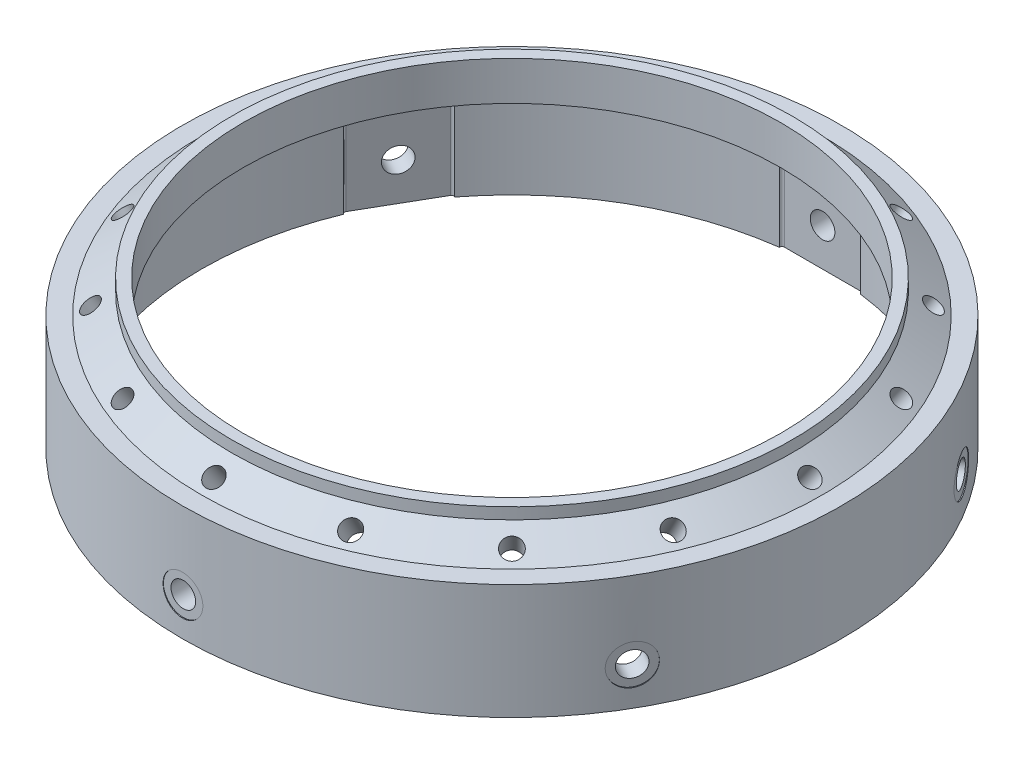
SolidWorks part; units mm, degrees
material "6061 Alloy"
ref_plane "Front Plane" through (0, 0, 0) normal (0, 0, 1) x (1, 0, 0)
ref_plane "Top Plane" through (0, 0, 0) normal (0, 1, 0) x (1, 0, 0)
ref_plane "Right Plane" through (0, 0, 0) normal (1, 0, 0) x (0, 0, -1)
sketch "Sketch1" plane through (0, 0, 0) normal (0, 0, 1) x (1, 0, 0)
  line L9 (0, 0) -> (0, -25.8501) construction
  line L18 (-87, 1) -> (-82, 1)
  line L19 (-82, 1) -> (-74, 6.6017)
  line L20 (-74, 6.6017) -> (-74, 9.6017)
  line L21 (-74, 9.6017) -> (-71, 9.6017)
  line L33 (-71, 9.6017) -> (-71, -0.6981)
  line L34 (-82, -8.4004) -> (-71, -0.6981)
  line L39 (-82, -8.4004) -> (-82, -29.4004)
  line L41 (-82, -29.4004) -> (-87, -29.4004)
  line L42 (-87, -29.4004) -> (-87, 1)
  dimension "D8" = 3
  dimension "D11" = 3
  dimension "D12" = 5
revolve "Revolve1" add sketch "Sketch1" angle 360 about L9
sketch "Sketch2" plane through (0, 0, 0) normal (0, 0, 1) x (1, 0, 0)
  line L0 (-74, 6.6017) -> (-82, 1) construction
  line L1 (-74, 6.6017) -> (-74, 1) construction
  line L2 (-74, 1) -> (-82, 1) construction
  point P4 (-78.671, 3.331)
  dimension "D1" = 4.671
hole_wizard "Ø4.2mm Dowel Hole1" positions "3DSketch1" profile "Sketch3" hole size "Ø5.0" standard "DIN" end condition up to next
sketch3d "3DSketch1"
  point P0 (-78.671, 3.331, 0)
sketch "Sketch3" plane through (-78.671, 3.331, 0) normal (0, 0, 1) x (-0.8192, -0.5736, 0)
  line L0 (0, 0) -> (0, 7.7004)
  line L1 (0, 7.7004) -> (2.5, 7.7004)
  line L2 (2.5, 7.7004) -> (2.5, 0)
  line L5 (2.5, 0) -> (0, 0)
  line L11 (0, -6.35) -> (0, 107.95) construction
  dimension "Thru Hole Dia." = 5
  dimension "Thru Hole Depth" = 7.7004
pattern_circular "CirPattern1" count 16 over 360 about axis through (0, 6.6017, 0) along (0, -1, 0) of "Ø4.2mm Dowel Hole1"
sketch "Szkic4" plane through (0, -29.4004, 0) normal (0, -1, 0) x (-1, 0, 0)
  line L0 (-4, -87) -> (4, -87)
  line L1 (0, -87) -> (0, -84.0434)
  line L2 (0, -84.0434) -> (4, -85.4333)
  line L3 (4, -85.4333) -> (4, -87)
  line L4 (-4, -85.4333) -> (-4, -87)
  line L5 (0, -84.0434) -> (-4, -85.4333)
  line L31 (-77.3442, -40.0359) -> (-73.3442, -46.9641)
  line L32 (-71.9874, -46.1808) -> (-73.3442, -46.9641)
  line L33 (-72.7837, -42.0217) -> (-71.9874, -46.1808)
  line L34 (-72.7837, -42.0217) -> (-75.9874, -39.2526)
  line L35 (-75.9874, -39.2526) -> (-77.3442, -40.0359)
  line L36 (-73.3442, 46.9641) -> (-77.3442, 40.0359)
  line L37 (-75.9874, 39.2526) -> (-77.3442, 40.0359)
  line L38 (-72.7837, 42.0217) -> (-75.9874, 39.2526)
  line L39 (-72.7837, 42.0217) -> (-71.9874, 46.1808)
  line L40 (-71.9874, 46.1808) -> (-73.3442, 46.9641)
  line L41 (4, 87) -> (-4, 87)
  line L42 (-4, 85.4333) -> (-4, 87)
  line L43 (0, 84.0434) -> (-4, 85.4333)
  line L44 (0, 84.0434) -> (4, 85.4333)
  line L45 (4, 85.4333) -> (4, 87)
  line L46 (77.3442, 40.0359) -> (73.3442, 46.9641)
  line L47 (71.9874, 46.1808) -> (73.3442, 46.9641)
  line L48 (72.7837, 42.0217) -> (71.9874, 46.1808)
  line L49 (72.7837, 42.0217) -> (75.9874, 39.2526)
  line L50 (75.9874, 39.2526) -> (77.3442, 40.0359)
  line L51 (73.3442, -46.9641) -> (77.3442, -40.0359)
  line L52 (75.9874, -39.2526) -> (77.3442, -40.0359)
  line L53 (72.7837, -42.0217) -> (75.9874, -39.2526)
  line L54 (72.7837, -42.0217) -> (71.9874, -46.1808)
  line L55 (71.9874, -46.1808) -> (73.3442, -46.9641)
  line L56 (0, 82) -> (-10.1, 82)
  line L57 (-10.1, 82) -> (-10.1, 79.6554)
  line L58 (-10.1, 79.6554) -> (10.1, 79.6554)
  line L59 (10.1, 79.6554) -> (10.1, 82)
  line L60 (10.1, 82) -> (0, 82)
  circle A0 centre (0, 0) radius 87 construction
  circle A1 centre (0, 0) radius 82 construction
  point P37 (0, 0)
  point P38 (0, 0)
  dimension "D1" = 6
sketch "Szkic2" plane through (0, 0, 0) normal (0, 0, 1) x (1, 0, 0)
  line L0 (0, -29.4004) -> (0, -19.4004)
  line L1 (-87, -29.4004) -> (87, -29.4004) construction
  circle A0 centre (0, -19.4004) radius 3.25
  dimension "D1" = 6.5
extrude "Wytnij-wyciągnięcie1" cut sketch "Szkic2" along normal blind 103 contours A0
pattern_circular "Szyk kołowy1" count 6 over 360 about axis through (0, 0, 0) along (0, 1, 0) of "Wytnij-wyciągnięcie1"
extrude "Wytnij-wyciągnięcie2" cut sketch "Szkic4" against normal blind 21 contours L60 L56 L57 L58 L59
pattern_circular "Szyk kołowy2" count 6 over 360 about axis through (0, 0, 0) along (0, 1, 0) of "Wytnij-wyciągnięcie2"
ref_plane "Plane1" through (0, 0, 87) normal (0, 0, 1) x (1, 0, 0)
sketch "Sketch4" plane through (0, 0, 87) normal (0, 0, 1) x (1, 0, 0)
  circle A0 centre (0, -19.4004) radius 3.25 construction
  circle A1 centre (0, -19.4004) radius 3.25
  circle A2 centre (0, -19.4004) radius 5.25
  dimension "D1" = 10.5
extrude "Cut-Extrude1" cut sketch "Sketch4" against normal blind 0.25 and the other way through all
pattern_circular "CirPattern2" count 6 over 360 about axis through (0, 0, 0) along (0, 1, 0) of "Cut-Extrude1"
sketch "Sketch5" plane through (-71.0141, 0, 41) normal (0.866, 0, -0.5) x (-0.5, 0, -0.866)
  line L0 (-10.1, -29.4004) -> (-10.72, -29.4004)
  line L1 (-10.72, -29.4004) -> (-10.72, -8.4004)
  line L2 (-10.72, -8.4004) -> (-10.1, -8.4004)
  line L3 (10.1, -8.4004) -> (10.72, -8.4004)
  line L4 (10.72, -8.4004) -> (10.72, -29.4004)
  line L5 (-10.1, -29.4004) -> (10.1, -29.4004)
  line L6 (10.1, -29.4004) -> (10.1, -8.4004)
  line L7 (10.1, -8.4004) -> (0, -8.4004)
  line L8 (0, -8.4004) -> (-10.1, -8.4004)
  line L9 (-10.1, -8.4004) -> (-10.1, -29.4004)
  line L10 (-10.1, -29.4004) -> (10.1, -29.4004)
  line L11 (10.1, -29.4004) -> (10.1, -8.4004)
  line L12 (10.1, -8.4004) -> (0, -8.4004)
  line L13 (0, -8.4004) -> (-10.1, -8.4004)
  line L14 (-10.1, -8.4004) -> (-10.1, -29.4004)
  line L15 (10.72, -29.4004) -> (10.1, -29.4004)
  line M10 (10.1, -29.4004) -> (10.1, -8.4004)
  line M13 (-10.1, -8.4004) -> (-10.1, -29.4004)
  dimension "D2" = 0.62
  dimension "D3" = 0.62
  dimension "D1" = 0
extrude "Cut-Extrude3" cut sketch "Sketch5" along normal blind 10 contours L2 L1 L0 M13 | L15 L4 L3 M10
fillet "Fillet1" radius 0.62 2 edges at (-76.3741, -18.9004, 31.7162) (-65.6541, -18.9004, 50.2838)
pattern_circular "CirPattern3" count 6 over 360 about axis through (0, 0, 0) along (0, 1, 0) of "Fillet1", "Cut-Extrude3"
equation "\"D1@Sketch2\"=4+cos(35)*cos(35)"
